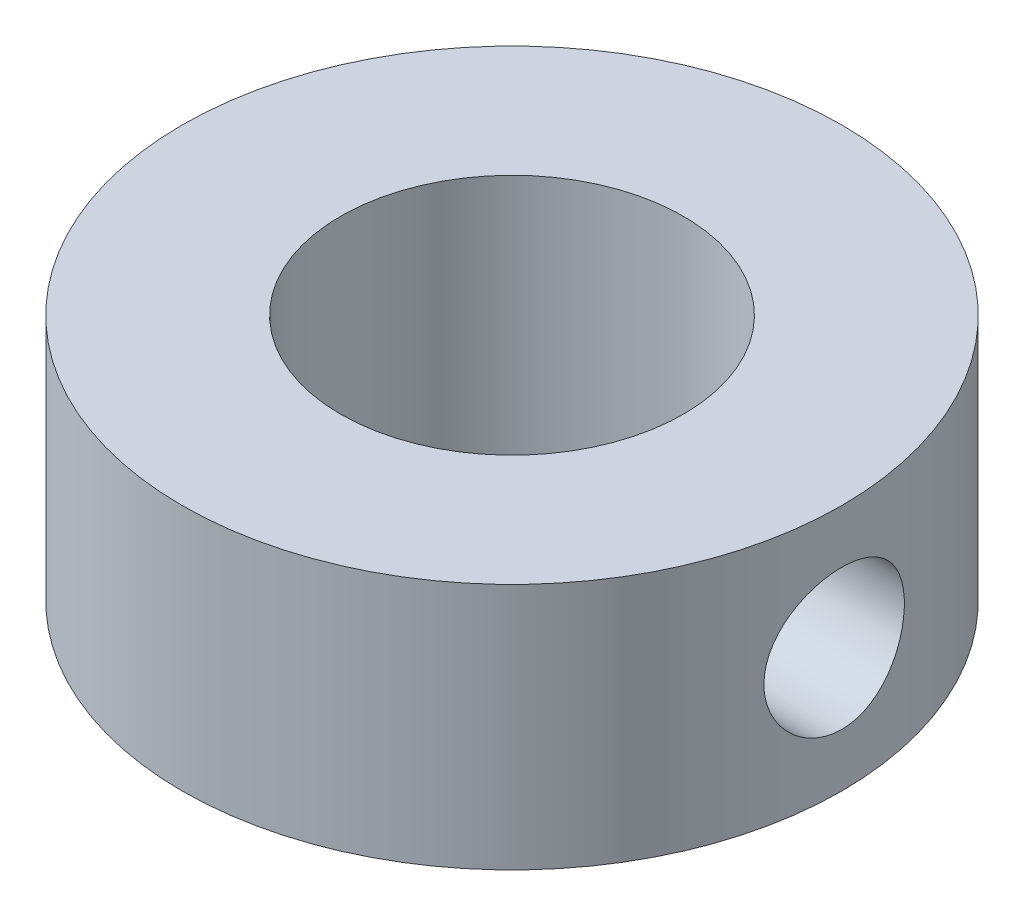
SolidWorks part; units mm, degrees
material "Polycarbonate"
ref_plane "Front Plane" through (0, 0, 0) normal (0, 0, 1) x (1, 0, 0)
ref_plane "Top Plane" through (0, 0, 0) normal (0, 1, 0) x (1, 0, 0)
ref_plane "Right Plane" through (0, 0, 0) normal (1, 0, 0) x (0, 0, -1)
sketch "Sketch1" plane through (0, 0, 0) normal (0, 1, 0) x (1, 0, 0)
  circle A0 centre (0, 0) radius 3.302
  circle A1 centre (0, 0) radius 6.35
  dimension "D1" = 6.604
  dimension "D2" = 12.7
extrude "Boss-Extrude1" add sketch "Sketch1" along normal blind 4.7625
hole_wizard "#6-32 Tapped Hole1" positions "Sketch2" profile "Sketch3" tap size "#6-32" standard "ANSI Inch"
sketch "Sketch2" plane through (0, 0, 0) normal (1, 0, 0) x (0, 0, -1)
  line L0 (6.35, 4.7625) -> (-6.35, 4.7625) construction
  line L1 (-6.35, 0) -> (6.35, 0) construction
  line L2 (6.35, 4.7625) -> (-6.35, 4.7625) construction
  line L3 (-6.35, 0) -> (6.35, 0) construction
  line L4 (0, 4.7625) -> (0, 0) construction
  point P0 (0, 2.3813)
sketch "Sketch3" plane through (0, 2.3813, 0) normal (0, 1, 0) x (0, 0, 1)
  line L0 (0, 0) -> (0, 6.35)
  line L1 (0, 6.35) -> (1.3525, 6.35)
  line L2 (1.3525, 6.35) -> (1.3525, 0)
  line L5 (1.3525, 0) -> (0, 0)
  line L11 (0, -6.35) -> (0, 107.95) construction
  dimension "Thru Tap Drill Dia." = 2.7051
  dimension "Thru Tap Drill Depth" = 6.35
cosmetic thread "Hole Thread1"
